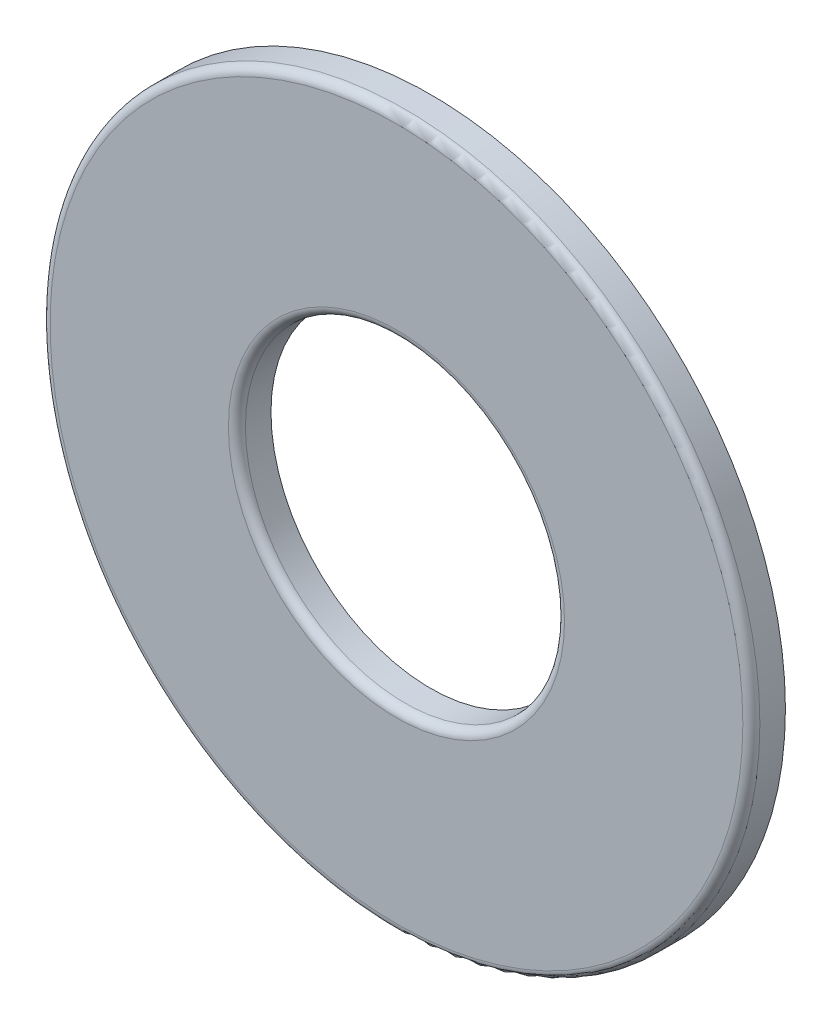
SolidWorks part; units mm, degrees
other "Imported1" parameters "D1"=0.1905, "TH"=1.0287, "Thickness"=0.762
material "AISI 316 Stainless Steel Sheet (SS)"
ref_plane "Front Plane" through (0, 0, 0) normal (0, 0, 1) x (1, 0, 0)
ref_plane "Top Plane" through (0, 0, 0) normal (0, 1, 0) x (1, 0, 0)
ref_plane "Right Plane" through (0, 0, 0) normal (1, 0, 0) x (0, 0, -1)
sketch "Sketch1" plane through (0, 0, 0) normal (0, 0, 1) x (1, 0, 0)
  line L0 (-7.9375, 0) -> (7.9375, 0) construction
  line L1 (-3.5687, 0) -> (3.5687, 0) construction
  circle A0 centre (0, 0) radius 3.5687 construction
  circle A1 centre (0, 0) radius 7.9375 construction
  point P8 (0, 0)
  point P9 (0, 7.9375)
  point P11 (3.5687, 0)
  dimension "ID" = 7.1374
  dimension "OD" = 15.875
sketch "Sketch2" plane through (0, 0, 0) normal (1, 0, 0) x (0, 0, -1)
  line L0 (-0.381, 7.9375) -> (0.381, 7.9375) construction
  point P2 (0, 7.9375)
sketch "Sketch3" plane through (0, 0, 0) normal (0, 0, 1) x (1, 0, 0)
  circle A0 centre (0, 0) radius 3.5687
  circle A1 centre (0, 0) radius 7.9375
extrude "Boss-Extrude1" add sketch "Sketch3" along normal up to vertex (0.381 mm away) and the other way up to vertex (0.381 mm away) up to point (0, 7.9375, 0.381) other way up to point (0, 7.9375, -0.381)
fillet "Fillet1" radius 0.1905 2 edges at (7.9375, 0, 0.381) (3.5687, 0, 0.381)
equation "\"D1@Fillet1\"=\"Thickness@Sketch2\"/4"
